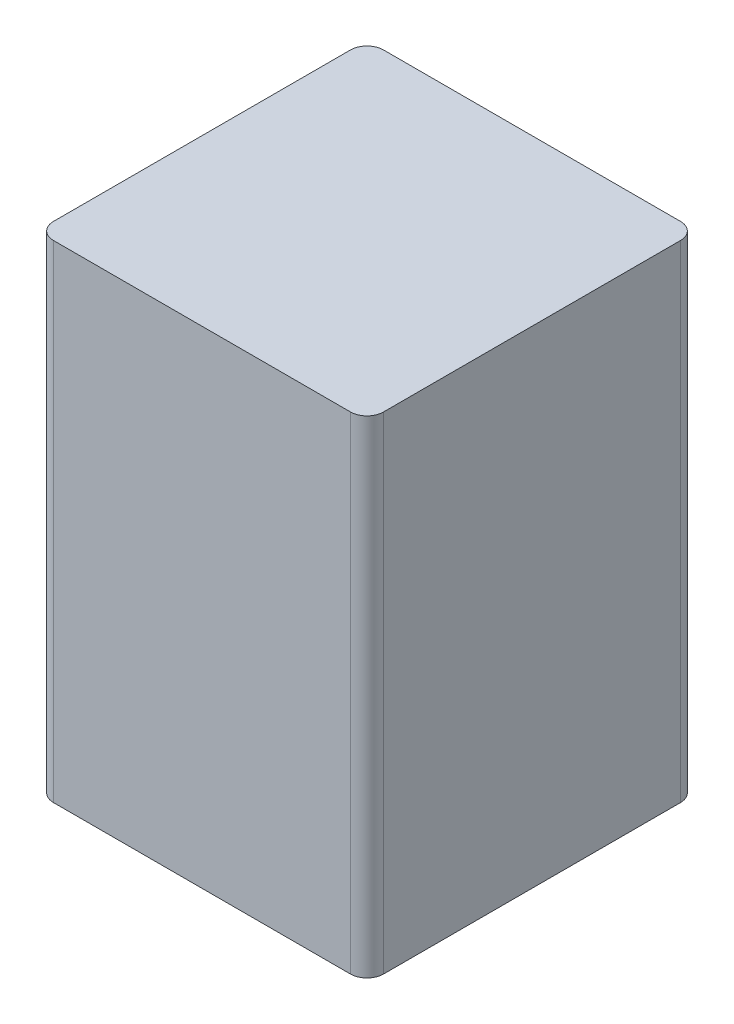
SolidWorks part; units mm, degrees
material "1060 Alloy"
ref_plane "Front Plane" through (0, 0, 0) normal (0, 0, 1) x (1, 0, 0)
ref_plane "Top Plane" through (0, 0, 0) normal (0, 1, 0) x (1, 0, 0)
ref_plane "Right Plane" through (0, 0, 0) normal (1, 0, 0) x (0, 0, -1)
sketch "Sketch1" plane through (0, 0, 0) normal (0, 1, 0) x (1, 0, 0)
  line L1 (-18.6087, -27.6957) -> (17.3913, -27.6957)
  line L2 (-20.6087, -25.6957) -> (-20.6087, 10.3043)
  line L3 (-18.6087, 12.3043) -> (17.3913, 12.3043)
  line L4 (19.3913, -25.6957) -> (19.3913, 10.3043)
  line L5 (-20.6087, -27.6957) -> (19.3913, 12.3043) construction
  line L6 (-20.6087, 12.3043) -> (19.3913, -27.6957) construction
  arc A0 (-20.6087, 10.3043) -> (-18.6087, 12.3043) centre (-18.6087, 10.3043) cw
  arc A1 (-18.6087, -27.6957) -> (-20.6087, -25.6957) centre (-18.6087, -25.6957) cw
  arc A2 (17.3913, -27.6957) -> (19.3913, -25.6957) centre (17.3913, -25.6957) ccw
  arc A3 (19.3913, 10.3043) -> (17.3913, 12.3043) centre (17.3913, 10.3043) ccw
  point P0 (-0.6087, -7.6957)
  dimension "D2" = 2
  dimension "D1" = 40
extrude "Boss-Extrude1" add sketch "Sketch1" along normal blind 59
sketch "Sketch2" plane through (0, 0, 0) normal (0, -1, 0) x (1, 0, 0)
  circle A0 centre (-0.6087, 7.6957) radius 5
  dimension "D1" = 10
extrude "Cut-Extrude1" cut sketch "Sketch2" against normal blind 4
